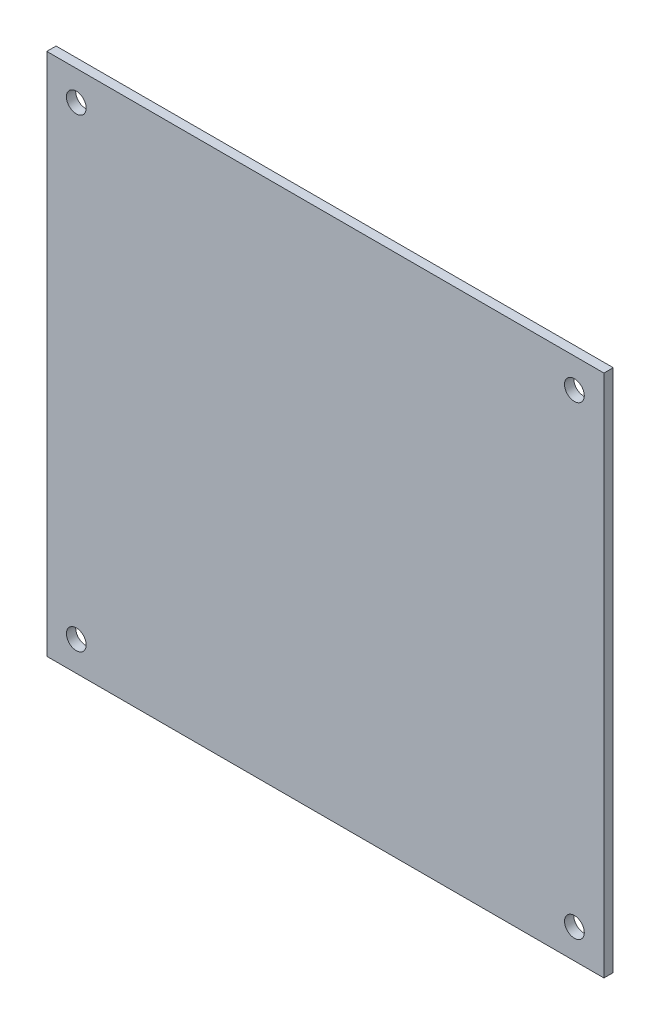
SolidWorks part; units mm, degrees
material "FR4 smeared radio v5"
ref_plane "Front Plane" through (0, 0, 0) normal (0, 0, 1) x (1, 0, 0)
ref_plane "Top Plane" through (0, 0, 0) normal (0, 1, 0) x (1, 0, 0)
ref_plane "Right Plane" through (0, 0, 0) normal (1, 0, 0) x (0, 0, -1)
sketch "Body sketch" plane through (0, 0, 0) normal (0, 0, 1) x (1, 0, 0)
  line L1 (0, 0) -> (95.89, 0)
  line L2 (0, 0) -> (0, 90.17)
  line L3 (0, 90.17) -> (95.89, 90.17)
  line L4 (95.89, 0) -> (95.89, 90.17)
extrude "Body" add sketch "Body sketch" along normal blind 1.6
sketch "Holes sketch" plane through (0, 0, 0) normal (0, 0, 1) x (1, 0, 0)
  circle A0 centre (5.08, 5.08) radius 1.7
  circle A1 centre (90.81, 5.08) radius 1.7
  circle A2 centre (5.08, 85.09) radius 1.7
  circle A3 centre (90.81, 85.09) radius 1.7
extrude "Holes" cut sketch "Holes sketch" against normal through all and the other way through all
